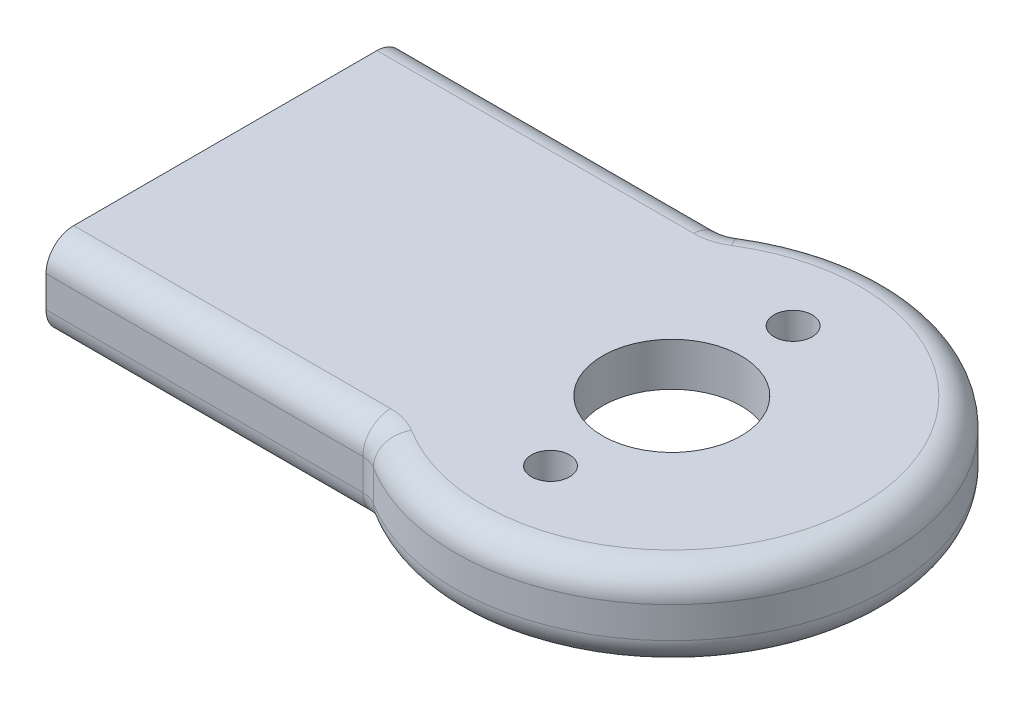
SolidWorks part; units mm, degrees
ref_plane "Alzado" through (0, 0, 0) normal (0, 0, 1) x (1, 0, 0)
ref_plane "Planta" through (0, 0, 0) normal (0, 1, 0) x (1, 0, 0)
ref_plane "Vista lateral" through (0, 0, 0) normal (1, 0, 0) x (0, 0, -1)
sketch "Croquis1" plane through (0, 0, 0) normal (0, 1, 0) x (1, 0, 0)
  line L0 (-1000, 0) -> (49000, 0) construction
  line L1 (-25.767, 6.35) -> (-10.767, 6.35) construction
  line L2 (-25.767, -6.35) -> (-10.767, -6.35) construction
  line L3 (-25.767, 10.35) -> (-7.0091, 10.35)
  line L4 (-32.3123, 10.35) -> (-10.767, 10.35) construction
  line L5 (-25.767, -10.35) -> (-7.0091, -10.35)
  line L6 (-32.3123, 6.35) -> (-10.767, 6.35) construction
  line L7 (-25.767, 10.35) -> (-25.767, -10.35)
  circle A0 centre (0, 0) radius 4
  arc A1 (-7.0091, -10.35) -> (-7.0091, 10.35) centre (0, 0) ccw
  circle A2 centre (0, 0) radius 10.5 construction
  circle A3 centre (0, 7) radius 1.1
  circle A4 centre (0, -7) radius 1.1
  point P14 (0, 0)
  dimension "D1" = 8
  dimension "D2" = 25
  dimension "D6" = 21
  dimension "D8" = 2.2
  dimension "D3" = 12.7
  dimension "D5" = 15
  dimension "D7" = 14
  dimension "D4" = 4
extrude "Saliente-Extruir1" add sketch "Croquis1" along normal mid plane 5
sketch "Croquis2" plane through (-25.767, 0, 0) normal (-1, 0, 0) x (0, 0, 1)
  line L0 (-6.55, 1) -> (6.55, 1)
  line L1 (-6.35, 0.8) -> (6.35, 0.8) construction
  line L2 (-6.35, 0.8) -> (-6.35, -0.8) construction
  line L3 (-6.35, -0.8) -> (6.35, -0.8) construction
  line L4 (6.35, 0.8) -> (6.35, -0.8) construction
  line L5 (-6.35, 0.8) -> (6.35, -0.8) construction
  line L6 (-6.35, -0.8) -> (6.35, 0.8) construction
  line L7 (6.55, 1) -> (6.55, -1)
  line L8 (-6.55, -1) -> (6.55, -1)
  line L9 (-6.55, 1) -> (-6.55, -1)
  point P0 (0, 0)
  dimension "D1" = 12.7
  dimension "D2" = 1.6
  dimension "D3" = 0.2
extrude "Cortar-Extruir1" cut sketch "Croquis2" against normal blind 15
sketch "Croquis3" plane through (0, 0, 0) normal (0, 1, 0) x (1, 0, 0)
  circle A2 centre (0, 0) radius 10.7
  circle A3 centre (0, 0) radius 10.7
  dimension "D1" = 0.2
extrude "Cortar-Extruir2" cut sketch "Croquis3" against normal up to next
fillet "Redondeo1" radius 1.6 8 edges at (-16.388, 2.5, 10.35) (-16.388, -2.5, 10.35) (-7.0091, 0, 10.35) (12.5, 2.5, 0) (12.5, -2.5, 0) (-7.0091, 0, -10.35) (-16.388, 2.5, -10.35) (-16.388, -2.5, -10.35)
